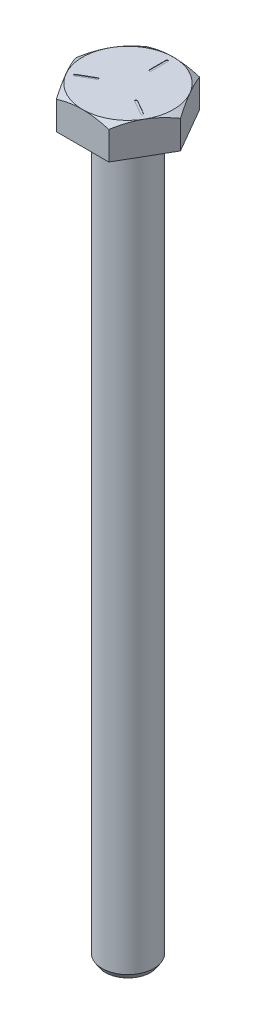
SolidWorks part; units mm, degrees
ref_plane "Front Plane" through (0, 0, 0) normal (0, 0, 1) x (1, 0, 0)
ref_plane "Top Plane" through (0, 0, 0) normal (0, 1, 0) x (1, 0, 0)
ref_plane "Right Plane" through (0, 0, 0) normal (1, 0, 0) x (0, 0, -1)
sketch "Sketch1" plane through (0, 0, 0) normal (0, 1, 0) x (1, 0, 0)
  line L1 (6.4158, 0) -> (3.2079, 5.5562)
  line L2 (3.2079, 5.5562) -> (-3.2079, 5.5562)
  line L3 (-3.2079, 5.5562) -> (-6.4158, 0)
  line L4 (-6.4158, 0) -> (-3.2079, -5.5563)
  line L5 (-3.2079, -5.5563) -> (3.2079, -5.5562)
  line L6 (3.2079, -5.5562) -> (6.4158, 0)
  circle A0 centre (0, 0) radius 5.5562 construction
  dimension "D1" = 11.1125
extrude "Boss-Extrude1" add sketch "Sketch1" along normal blind 3.9624
sketch "Sketch2" plane through (0, 0, 0) normal (0, 0, 1) x (1, 0, 0)
  line L0 (5.5563, 3.9624) -> (6.4158, 3.4544)
  line L2 (6.4158, 3.9624) -> (6.4158, 0) construction
  line L3 (6.4158, 3.4544) -> (6.4158, 3.9624)
  line L4 (6.4158, 3.9624) -> (5.5563, 3.9624)
  line L5 (0, 0) -> (0, 3.9624) construction
  line L6 (-3.2079, 0) -> (3.2079, 0) construction
  line L7 (-3.2079, 3.9624) -> (3.2079, 3.9624) construction
  line L8 (6.4158, 3.9624) -> (6.4158, 0) construction
  line L9 (3.2079, 3.9624) -> (6.4158, 3.9624) construction
  dimension "D1" = 5.5562
  dimension "D2" = 0.508
revolve "Cut-Revolve1" cut sketch "Sketch2" angle 360 about L5
sketch "Sketch3" plane through (0, 3.9624, 0) normal (0, -1, 0) x (-1, 0, 0)
  line L0 (0, 4.7625) -> (0, 2.7305) construction
  line L1 (0.127, 4.7625) -> (0.127, 2.7305)
  line L2 (-0.127, 4.7625) -> (-0.127, 2.7305)
  line L3 (4.1244, -2.3812) -> (2.3647, -1.3652) construction
  line L4 (4.0609, -2.4912) -> (2.3012, -1.4752)
  line L5 (4.1879, -2.2713) -> (2.4282, -1.2553)
  line L6 (-4.1244, -2.3812) -> (-2.3647, -1.3652) construction
  line L7 (-4.1879, -2.2713) -> (-2.4282, -1.2553)
  line L8 (-4.0609, -2.4912) -> (-2.3012, -1.4752)
  arc A0 (0.127, 4.7625) -> (-0.127, 4.7625) centre (0, 4.7625) ccw
  arc A1 (-0.127, 2.7305) -> (0.127, 2.7305) centre (0, 2.7305) ccw
  arc A2 (4.0609, -2.4912) -> (4.1879, -2.2713) centre (4.1244, -2.3812) ccw
  arc A3 (2.4282, -1.2553) -> (2.3012, -1.4752) centre (2.3647, -1.3652) ccw
  arc A4 (-4.1879, -2.2713) -> (-4.0609, -2.4912) centre (-4.1244, -2.3812) ccw
  arc A5 (-2.3012, -1.4752) -> (-2.4282, -1.2553) centre (-2.3647, -1.3652) ccw
  point P3 (0, 3.7465)
  point P12 (3.2446, -1.8732)
  point P19 (-3.2446, -1.8732)
  point P24 (0, 0)
  dimension "D1" = 0.127
  dimension "D2" = 2.032
  dimension "D3" = 4.7625
  dimension "D4" = 3
extrude "Cut-Extrude1" cut sketch "Sketch3" along normal blind 0.0508
sketch "Sketch6" plane through (0, 0, 0) normal (0, 0, 1) x (1, 0, 0)
  line L0 (0, 0) -> (0, 3.302)
  line L1 (0, 3.302) -> (2.7381, 3.302)
  line L3 (3.2079, 3.9624) -> (6.4158, 3.9624) construction
  line L5 (5.4445, 0) -> (5.526, 0.4016)
  line L8 (6.4158, 0) -> (5.4445, 0)
  line L9 (-3.2079, 0) -> (3.2079, 0) construction
  line L10 (0, 3.302) -> (0, 3.9624)
  line L11 (0, 3.9624) -> (5.5563, 3.9624)
  line L12 (5.5562, 3.9624) -> (4.8119, 3.9624) construction
  line L13 (5.5563, 3.9624) -> (6.4158, 3.4544)
  line L14 (6.4158, 3.4544) -> (6.4158, 0)
  line L15 (0, 3.9624) -> (0, 3.302)
  arc A0 (2.8154, 3.2831) -> (5.5127, 0.508) centre (-0.014, -2.1652) cw
  arc A1 (2.7381, 3.302) -> (2.8154, 3.2831) centre (2.7381, 3.1344) cw
  arc A2 (5.526, 0.4016) -> (5.5127, 0.508) centre (5.3617, 0.435) ccw
  point P13 (2.7788, 3.302)
  point P16 (5.5372, 0.4566)
  dimension "D6" = 6.1392
  dimension "D7" = 0.1676
  dimension "D1" = 0.508
  dimension "D2" = 2.7788
  dimension "D3" = 101.48
  dimension "D4" = 5.5372
  dimension "D5" = 3.302
revolve "Cut-Revolve2" [suppressed] cut sketch "Sketch6" angle 360 about L0
sketch "Sketch7" [suppressed] plane through (0, 2.5654, 0) normal (0, 1, 0) x (1, 0, 0)
  line L1 (1.8331, 0) -> (0.9165, 1.5875)
  line L2 (0.9165, 1.5875) -> (-0.9165, 1.5875)
  line L3 (-0.9165, 1.5875) -> (-1.8331, 0)
  line L4 (-1.8331, 0) -> (-0.9165, -1.5875)
  line L5 (-0.9165, -1.5875) -> (0.9165, -1.5875)
  line L6 (0.9165, -1.5875) -> (1.8331, 0)
  circle A0 centre (0, 0) radius 1.5875 construction
  dimension "D1" = 3.9688
extrude "Cut-Extrude2" [suppressed] cut sketch "Sketch7" against normal blind 1.524
sketch "Sketch8" [suppressed] plane through (0, 0, 0) normal (0, 0, 1) x (1, 0, 0)
  line L0 (-1.8331, 2.5654) -> (-1.5283, 2.3876)
  line L1 (-1.5283, 2.3876) -> (-1.5283, 2.5654)
  line L2 (-1.5283, 2.5654) -> (-1.8331, 2.5654)
  line L3 (0, 0) -> (0, -30.4461) construction
  line L4 (-1.5283, 2.3876) -> (0, 2.3876)
  line L5 (0, 2.3876) -> (0, 2.5654)
  line L6 (0, 2.5654) -> (-1.5283, 2.5654)
  dimension "D1" = 0.1778
  dimension "D2" = 0.3048
revolve "Cut-Revolve3" [suppressed] cut sketch "Sketch8" angle 360 about L3
sketch "Sketch9" [suppressed] plane through (0, 3.9624, 0) normal (0, 1, 0) x (-1, 0, 0)
  line L0 (-4.8119, 2.7781) -> (-6.4158, 0) construction
  line L1 (-6.4158, 0) -> (-4.8119, -2.7781) construction
  line L2 (-4.8119, -2.7781) -> (-3.2079, -5.5562) construction
  line L3 (-3.2079, -5.5562) -> (0, -5.5563) construction
  line L4 (3.2079, -5.5562) -> (4.8119, -2.7781) construction
  line L5 (0, -5.5563) -> (3.2079, -5.5562) construction
  line L6 (6.4158, 0) -> (4.8119, 2.7781) construction
  line L7 (4.8119, -2.7781) -> (6.4158, 0) construction
  line L8 (3.2079, 5.5563) -> (0, 5.5563) construction
  line L9 (4.8119, 2.7781) -> (3.2079, 5.5563) construction
  line L10 (0, 5.5563) -> (-3.2079, 5.5562) construction
  line L11 (-3.2079, 5.5562) -> (-4.8119, 2.7781) construction
  line L12 (-4.8119, 2.7781) -> (-6.4158, 0)
  line L13 (-6.4158, 0) -> (-4.8119, -2.7781)
  line L14 (-4.8119, -2.7781) -> (-3.2079, -5.5562)
  line L15 (-3.2079, -5.5562) -> (0, -5.5563)
  line L16 (3.2079, -5.5562) -> (4.8119, -2.7781)
  line L17 (0, -5.5563) -> (3.2079, -5.5562)
  line L18 (6.4158, 0) -> (4.8119, 2.7781)
  line L19 (4.8119, -2.7781) -> (6.4158, 0)
  line L20 (3.2079, 5.5563) -> (0, 5.5563)
  line L21 (4.8119, 2.7781) -> (3.2079, 5.5563)
  line L22 (0, 5.5563) -> (-3.2079, 5.5562)
  line L23 (-3.2079, 5.5562) -> (-4.8119, 2.7781)
  circle A0 centre (0, 0) radius 3.9688
  arc A1 (-4.8119, 2.7781) -> (-4.8119, -2.7781) centre (0, 0) ccw construction
  arc A2 (-4.8119, -2.7781) -> (0, -5.5563) centre (0, 0) ccw construction
  arc A3 (0, -5.5563) -> (4.8119, -2.7781) centre (0, 0) ccw construction
  arc A4 (4.8119, -2.7781) -> (4.8119, 2.7781) centre (0, 0) ccw construction
  arc A5 (4.8119, 2.7781) -> (0, 5.5563) centre (0, 0) ccw construction
  arc A6 (0, 5.5563) -> (-4.8119, 2.7781) centre (0, 0) ccw construction
  arc A7 (-4.8119, 2.7781) -> (-4.8119, -2.7781) centre (0, 0) ccw
  arc A8 (-4.8119, -2.7781) -> (0, -5.5563) centre (0, 0) ccw
  arc A9 (0, -5.5563) -> (4.8119, -2.7781) centre (0, 0) ccw
  arc A10 (4.8119, -2.7781) -> (4.8119, 2.7781) centre (0, 0) ccw
  arc A11 (4.8119, 2.7781) -> (0, 5.5563) centre (0, 0) ccw
  arc A12 (0, 5.5563) -> (-4.8119, 2.7781) centre (0, 0) ccw
  dimension "D1" = 9.525
extrude "Cut-Extrude3" [suppressed] cut sketch "Sketch9" against normal through all
sketch "Sketch11" [suppressed] plane through (0, 3.9624, 0) normal (0, -1, 0) x (-1, 0, 0)
  circle A0 centre (0, 0) radius 3.9688 construction
  circle A1 centre (0, 0) radius 3.9688
extrude "Boss-Extrude3" [suppressed] add sketch "Sketch11" against normal blind 2.3876
sketch "Sketch12" [suppressed] plane through (0, 6.35, 0) normal (0, -1, 0) x (-1, 0, 0)
  line L1 (2.2914, 0) -> (1.1457, 1.9844)
  line L2 (1.1457, 1.9844) -> (-1.1457, 1.9844)
  line L3 (-1.1457, 1.9844) -> (-2.2914, 0)
  line L4 (-2.2914, 0) -> (-1.1457, -1.9844)
  line L5 (-1.1457, -1.9844) -> (1.1457, -1.9844)
  line L6 (1.1457, -1.9844) -> (2.2914, 0)
  circle A0 centre (0, 0) radius 1.9844 construction
  dimension "D1" = 4.7625
extrude "Cut-Extrude4" [suppressed] cut sketch "Sketch12" along normal blind 3.175
fillet "Fillet1" [suppressed] radius 0.3175
sketch "Sketch14" [suppressed] plane through (0, 0, 0) normal (0, 0, 1) x (1, 0, 0)
  line L0 (-2.3454, 5.9531) -> (-3.0328, 6.35)
  line L1 (3.6513, 6.35) -> (-3.6513, 6.35) construction
  line L2 (-3.0328, 6.35) -> (0, 6.35)
  line L3 (0, 6.35) -> (0, 5.9531)
  line L5 (0, 5.9531) -> (-2.3454, 5.9531)
  dimension "D1" = 3.0328
  dimension "D2" = 30
  dimension "D3" = 0.7937
revolve "Cut-Revolve4" [suppressed] cut sketch "Sketch14" angle 360 about L3
sketch "Bolt Length Sketch" plane through (0, 0, 0) normal (0, 0, 1) x (1, 0, 0)
  line L0 (0, 0) -> (0, -88.9)
  line L1 (0, -88.9) -> (2.7781, -88.9)
  line L2 (2.7781, -88.9) -> (3.175, -88.265)
  line L3 (3.175, -88.265) -> (3.175, 0)
  line L6 (0, 0) -> (3.175, 0)
  dimension "D1" = 3.175
  dimension "D2" = 0.635
  dimension "D3" = 0.3969
  dimension "D4" = 88.9
revolve "Bolt Length" add sketch "Bolt Length Sketch" angle 360 about L0
